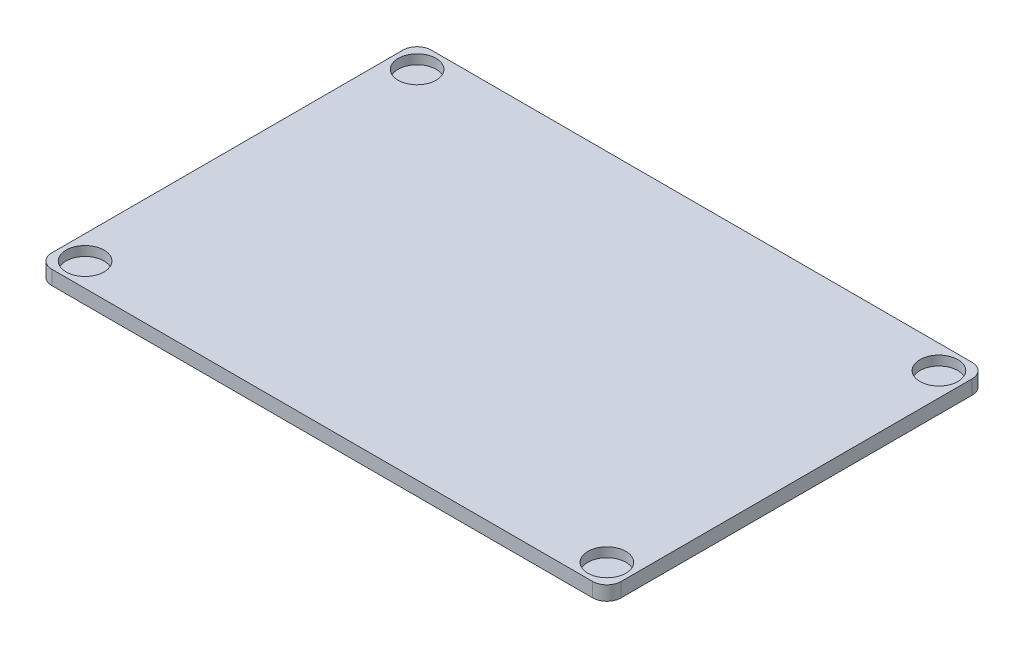
SolidWorks part; units mm, degrees
ref_plane "Front Plane" through (0, 0, 0) normal (0, 0, 1) x (1, 0, 0)
ref_plane "Top Plane" through (0, 0, 0) normal (0, 1, 0) x (1, 0, 0)
ref_plane "Right Plane" through (0, 0, 0) normal (1, 0, 0) x (0, 0, -1)
sketch "Sketch1" plane through (0, 0, 0) normal (0, 1, 0) x (1, 0, 0)
  line L1 (0, 0) -> (120, 0)
  line L2 (0, 0) -> (0, 80)
  line L3 (0, 80) -> (120, 80)
  line L4 (120, 0) -> (120, 80)
  dimension "D1" = 80
  dimension "D2" = 120
extrude "Boss-Extrude1" add sketch "Sketch1" along normal blind 3
sketch "Sketch2" plane through (0, 3, 0) normal (0, 1, 0) x (1, 0, 0)
  circle A3 centre (5, 75) radius 4
extrude "Cut-Extrude1" cut sketch "Sketch2" against normal blind 2
ref_plane "Plane1" through (0, 0, -40) normal (0, 0, -1) x (-1, 0, 0)
mirror "Mirror1" about plane through (0, 0, -40) normal (0, 0, -1) of "Cut-Extrude1"
ref_plane "Plane2" through (60, 0, 0) normal (-1, 0, 0) x (0, 0, 1)
mirror "Mirror2" about plane through (60, 0, 0) normal (-1, 0, 0) of "Mirror1", "Cut-Extrude1"
fillet "Fillet2" radius 3 4 edges at (0, 1.5, 0) (0, 1.5, -80) (120, 1.5, -80) (120, 1.5, 0)
